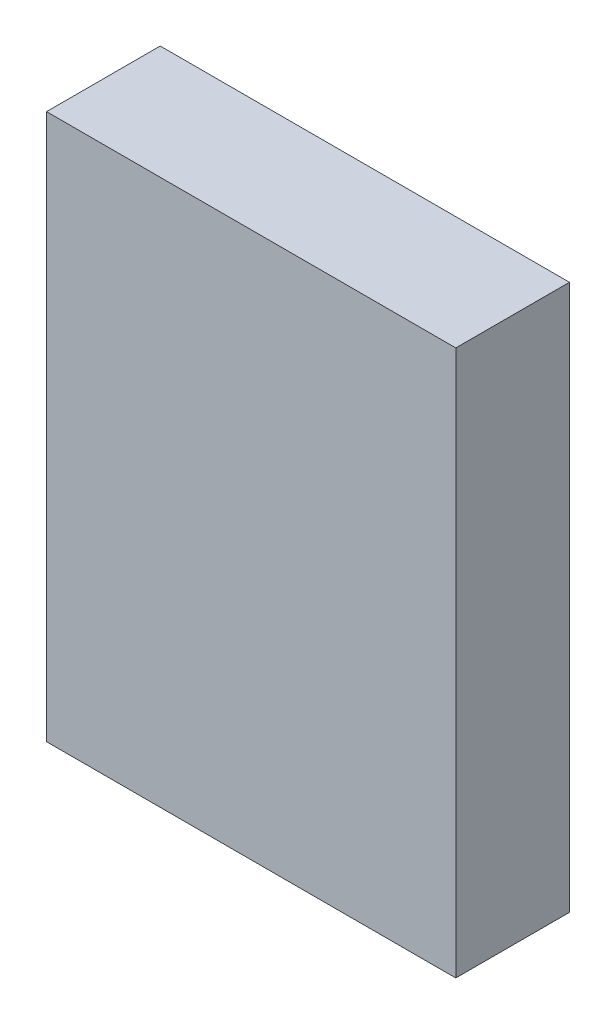
SolidWorks part; units mm, degrees
ref_plane "Front Plane" through (0, 0, 0) normal (0, 0, 1) x (1, 0, 0)
ref_plane "Top Plane" through (0, 0, 0) normal (0, 1, 0) x (1, 0, 0)
ref_plane "Right Plane" through (0, 0, 0) normal (1, 0, 0) x (0, 0, -1)
sketch "Sketch1" plane through (0, 0, 0) normal (0, 0, 1) x (1, 0, 0)
  line L1 (-151.7743, 6.9115) -> (-133.7743, 6.9115)
  line L2 (-151.7743, 6.9115) -> (-151.7743, -17.0885)
  line L3 (-151.7743, -17.0885) -> (-133.7743, -17.0885)
  line L4 (-133.7743, 6.9115) -> (-133.7743, -17.0885)
  line L5 (-151.7743, 6.9115) -> (-133.7743, -17.0885) construction
  line L6 (-151.7743, -17.0885) -> (-133.7743, 6.9115) construction
  point P0 (-142.7743, -5.0885)
  dimension "D1" = 24
  dimension "D2" = 18
extrude "Boss-Extrude1" add sketch "Sketch1" along normal blind 5
